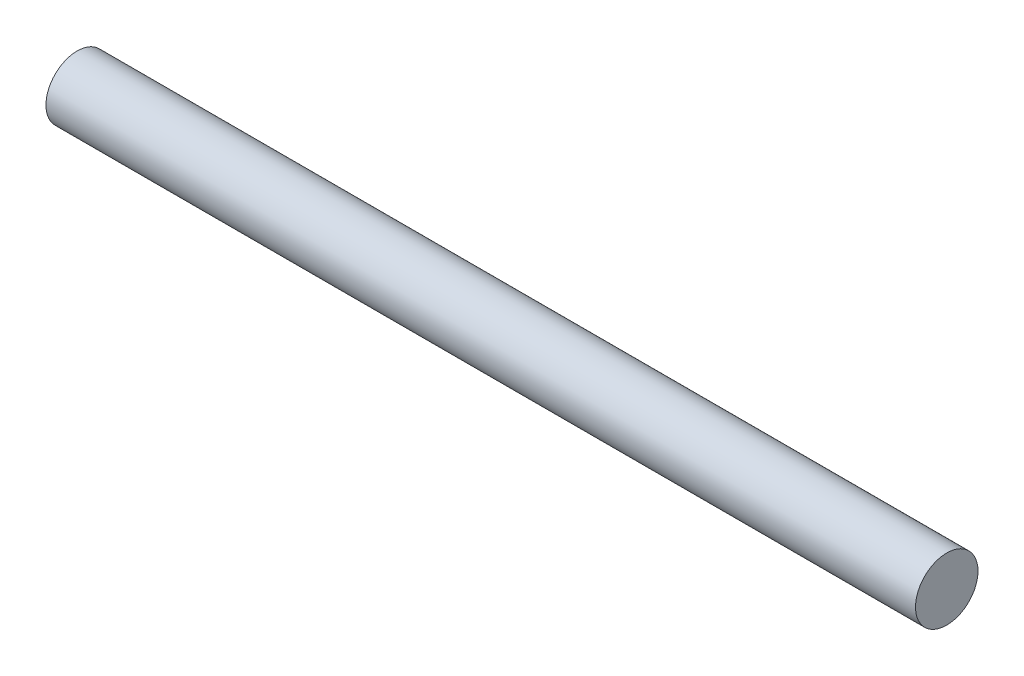
SolidWorks part; units mm, degrees
material "Stainless Steel (ferritic)"
ref_plane "Front Plane" through (0, 0, 0) normal (0, 0, 1) x (1, 0, 0)
ref_plane "Top Plane" through (0, 0, 0) normal (0, 1, 0) x (1, 0, 0)
ref_plane "Right Plane" through (0, 0, 0) normal (1, 0, 0) x (0, 0, -1)
sketch "Sketch1" plane through (0, 0, 0) normal (1, 0, 0) x (0, 0, -1)
  circle A0 centre (0, 0) radius 1.5
  dimension "D1" = 3
extrude "Boss-Extrude1" add sketch "Sketch1" along normal blind 41.73 contours A0
